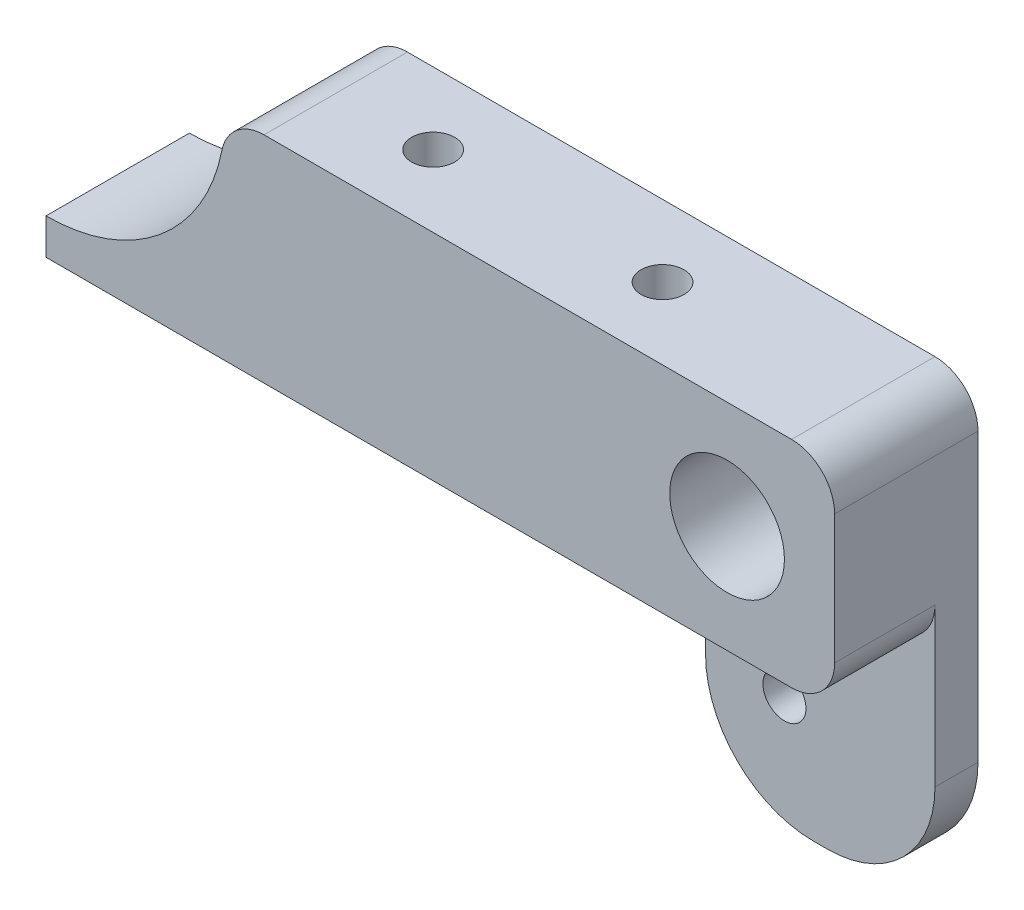
SolidWorks part; units mm, degrees
material "Aleación 6061"
ref_plane "Alzado" through (0, 0, 0) normal (0, 0, 1) x (1, 0, 0)
ref_plane "Planta" through (0, 0, 0) normal (0, 1, 0) x (1, 0, 0)
ref_plane "Vista lateral" through (0, 0, 0) normal (1, 0, 0) x (0, 0, -1)
sketch "Croquis1" plane through (0, 0, 0) normal (0, 0, 1) x (1, 0, 0)
  line L1 (-35, 7.5) -> (7.5, 7.5)
  line L2 (-47.5, -5) -> (-47.5, -7.5)
  line L3 (-47.5, -7.5) -> (7.5, -7.5)
  line L4 (7.5, 7.5) -> (7.5, -7.5)
  circle A0 centre (0, 0) radius 4
  arc A1 (-47.5, -5) -> (-35, 7.5) centre (-47.5, 7.5) ccw
  point P4 (7.5, 0)
  dimension "D3" = 8
  dimension "D5" = 25
  dimension "D1" = 55
  dimension "D2" = 15
  dimension "D4" = 7.5
extrude "Saliente-Extruir1" add sketch "Croquis1" along normal blind 10
sketch "Croquis3" plane through (0, 0, 0) normal (0, 0, 1) x (1, 0, 0)
  line L1 (7.5, -7.5) -> (-8.5, -7.5)
  line L2 (7.5, -7.5) -> (7.5, -23)
  line L3 (7.5, -23) -> (-8.5, -23)
  line L4 (-8.5, -7.5) -> (-8.5, -23)
  circle A0 centre (-3, -15.25) radius 1.5
  dimension "D3" = 3
  dimension "D1" = 16
  dimension "D2" = 15.5
  dimension "D4" = 7.75
  dimension "D5" = 5.5
extrude "Saliente-Extruir2" add sketch "Croquis3" along normal blind 3
fillet "Redondeo1" radius 7.5 2 edges at (-8.5, -23, 1.5) (7.5, -23, 1.5)
fillet "Redondeo2" radius 3 1 edges at (-8.5, -7.5, 1.5)
sketch "Croquis4" plane through (0, 7.5, 0) normal (0, 1, 0) x (1, 0, 0)
  line L0 (7.5, -10) -> (7.5, 0) construction
  circle A0 centre (-25.5, -5) radius 1.5
  circle A1 centre (-9.5, -5) radius 1.5
  point P5 (7.5, -5)
  dimension "D1" = 3
  dimension "D2" = 33
  dimension "D3" = 16
extrude "Cortar-Extruir2" cut sketch "Croquis4" against normal up to surface (15 mm away) up to face at (-17.1667, -7.5, 4.3333)
fillet "Redondeo3" radius 3 3 edges at (-35, 7.5, 5) (7.5, -7.5, 6.5) (7.5, 7.5, 5)
equation "\"D4@Croquis1\"=\"D2@Croquis1\"/2"
equation "\"D4@Croquis3\"=\"D2@Croquis3\"/2"
